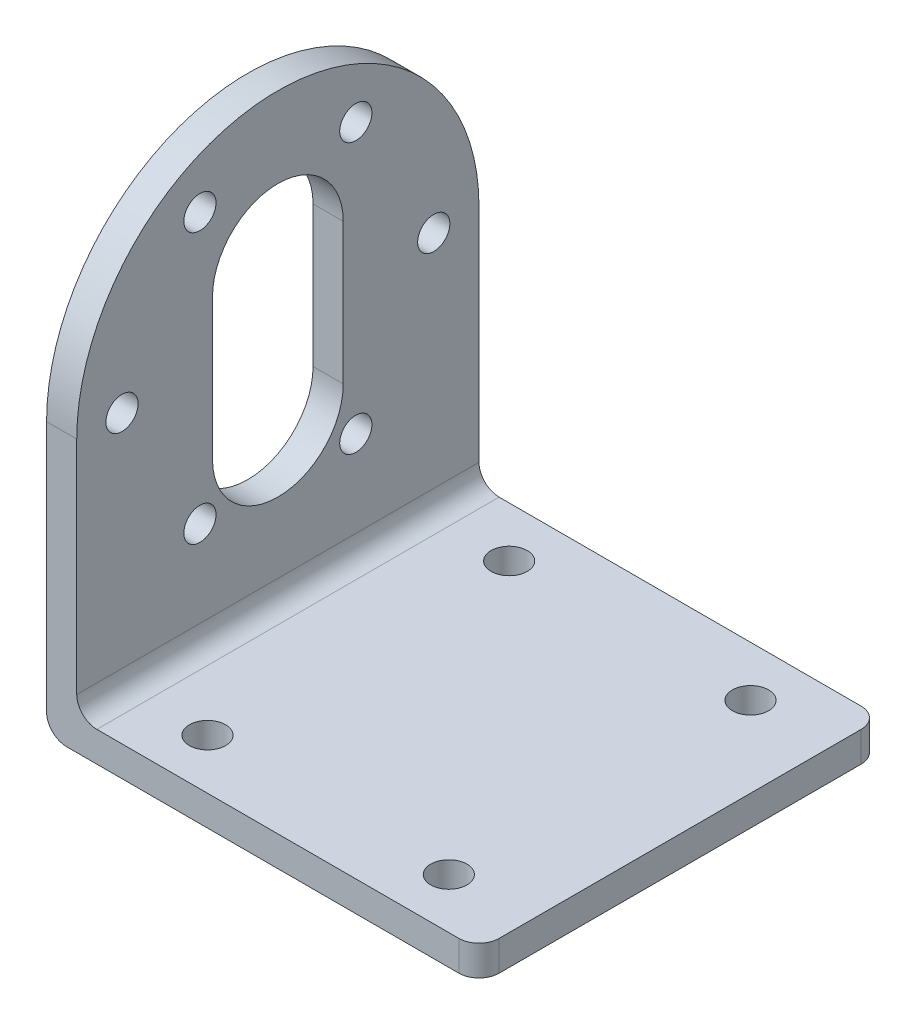
SolidWorks part; units mm, degrees
ref_plane "前视基准面" through (0, 0, 0) normal (0, 0, 1) x (1, 0, 0)
ref_plane "上视基准面" through (0, 0, 0) normal (0, 1, 0) x (1, 0, 0)
ref_plane "右视基准面" through (0, 0, 0) normal (1, 0, 0) x (0, 0, -1)
sketch "草图1" plane through (0, 0, 0) normal (1, 0, 0) x (0, 0, -1)
  line L0 (-20, 0) -> (20, 0)
  line L1 (-20, 0) -> (-20, 27)
  line L2 (0, 55) -> (0, -55) construction
  line L3 (20, 0) -> (20, 27)
  line L4 (0, 32.5) -> (0, 18.5) construction
  line L7 (-7.75, 40.4234) -> (0, 27) construction
  line L10 (6.5, 32.5) -> (6.5, 18.5)
  line L11 (-6.5, 32.5) -> (-6.5, 18.5)
  arc A0 (-20, 27) -> (20, 27) centre (0, 27) cw
  circle A3 centre (0, 27) radius 15.5 construction
  arc A10 (6.5, 32.5) -> (-6.5, 32.5) centre (0, 32.5) ccw
  arc A11 (-6.5, 18.5) -> (6.5, 18.5) centre (0, 18.5) ccw
  circle A12 centre (-7.75, 40.4234) radius 1.6
  circle A18 centre (7.75, 40.4234) radius 1.6
  circle A19 centre (15.5, 27) radius 1.6
  circle A20 centre (7.75, 13.5766) radius 1.6
  circle A21 centre (-7.75, 13.5766) radius 1.6
  circle A22 centre (-15.5, 27) radius 1.6
  point P4 (0, 0)
  point P9 (0, 25.5)
  point P19 (0, 0)
  point P20 (0, 47)
  point P31 (0, 27.5)
  point P34 (0, 27)
  dimension "D3" = 20
  dimension "D5" = 25.5
  dimension "D6" = 31
  dimension "D7" = 3.2
  dimension "D8" = 6.5
  dimension "D9" = 30
  dimension "D1" = 40
  dimension "D2" = 47
  dimension "D4" = 14
  dimension "D10" = 6
extrude "凸台-拉伸1" add sketch "草图1" along normal blind 3
sketch "草图2" plane through (0, 0, 0) normal (0, -1, 0) x (1, 0, 0)
  line L1 (0, 20) -> (41, 20)
  line L2 (0, 20) -> (0, -20)
  line L3 (0, -20) -> (41, -20)
  line L4 (43, 18) -> (43, -18)
  line L5 (11, 15) -> (35, 15) construction
  line L6 (11, 15) -> (11, -15) construction
  line L7 (11, -15) -> (35, -15) construction
  line L8 (35, 15) -> (35, -15) construction
  circle A0 centre (11, 15) radius 1.8
  circle A1 centre (35, 15) radius 1.8
  circle A2 centre (11, -15) radius 1.8
  circle A3 centre (35, -15) radius 1.8
  arc A4 (41, -20) -> (43, -18) centre (41, -18) ccw
  arc A5 (41, 20) -> (43, 18) centre (41, 18) cw
  point P1 (43, 0)
  point P9 (35, 0)
  dimension "D5" = 3.6
  dimension "D6" = 3.6
  dimension "D7" = 3.6
  dimension "D8" = 3.6
  dimension "D9" = 2
  dimension "D1" = 8
  dimension "D2" = 40
  dimension "D3" = 30
  dimension "D4" = 24
  dimension "D10" = 43
extrude "凸台-拉伸2" add sketch "草图2" against normal blind 3
fillet "圆角1" radius 2 2 edges at (3, 3, 0) (0, 0, 0)
